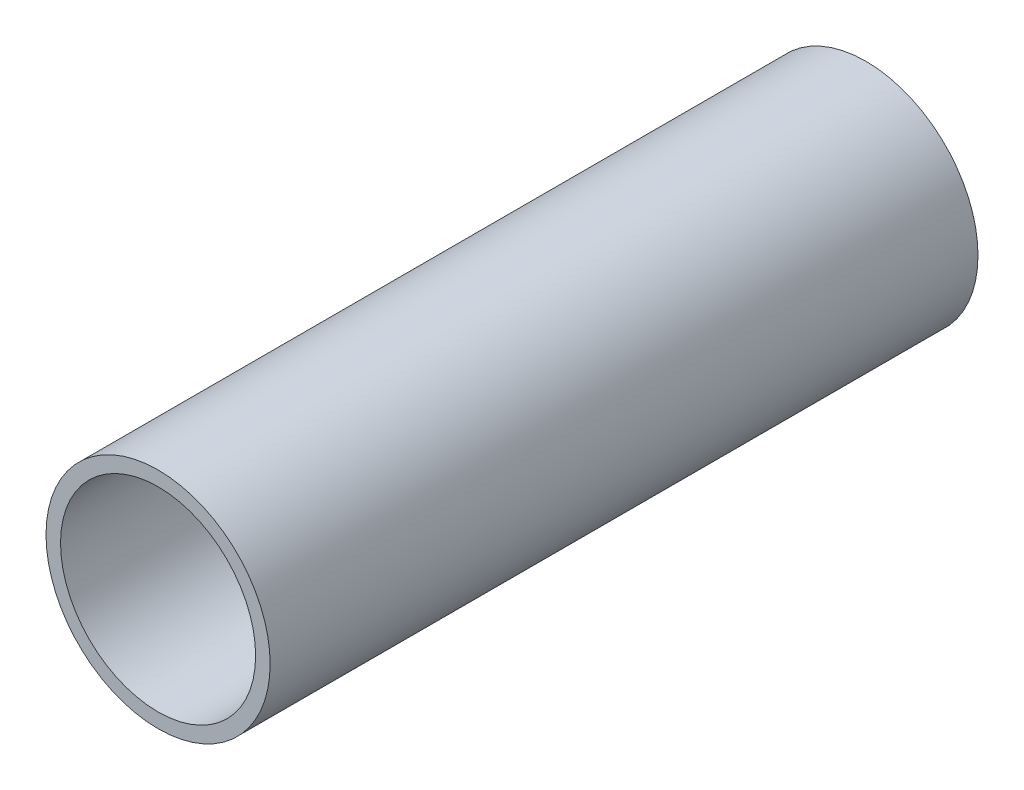
SolidWorks part; units mm, degrees
ref_plane "Front Plane" through (0, 0, 0) normal (0, 0, 1) x (1, 0, 0)
ref_plane "Top Plane" through (0, 0, 0) normal (0, 1, 0) x (1, 0, 0)
ref_plane "Right Plane" through (0, 0, 0) normal (1, 0, 0) x (0, 0, -1)
sketch "Sketch1" plane through (0, 0, 0) normal (0, 0, 1) x (1, 0, 0)
  circle A0 centre (0, 0) radius 30.1625
  circle A1 centre (0, 0) radius 26.2509
  dimension "D1" = 60.325
  dimension "D2" = 3.9116
extrude "Boss-Extrude1" add sketch "Sketch1" along normal blind 190.5
